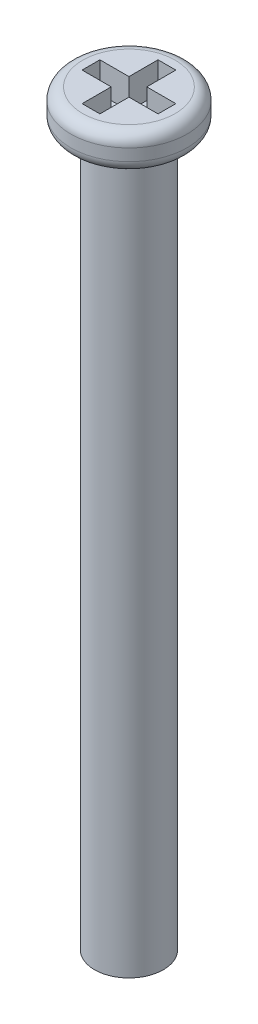
SolidWorks part; units mm, degrees
ref_plane "Front Plane" through (0, 0, 0) normal (0, 0, 1) x (1, 0, 0)
ref_plane "Top Plane" through (0, 0, 0) normal (0, 1, 0) x (1, 0, 0)
ref_plane "Right Plane" through (0, 0, 0) normal (1, 0, 0) x (0, 0, -1)
sketch "Sketch1" plane through (0, 0, 0) normal (0, 1, 0) x (1, 0, 0)
  circle A0 centre (0, 0) radius 1.45
  dimension "D1" = 2.9
extrude "Boss-Extrude1" add sketch "Sketch1" along normal blind 30
sketch "Sketch2" plane through (0, 30, 0) normal (0, 1, 0) x (1, 0, 0)
  circle A0 centre (0, 0) radius 2.45
  dimension "D1" = 4.9
extrude "Boss-Extrude2" add sketch "Sketch2" along normal blind 1.5
fillet "Fillet1" radius 0.5 2 edges at (0, 30, 2.45) (0, 31.5, 2.45)
sketch "Sketch3" plane through (0, 31.5, 0) normal (0, 1, 0) x (1, 0, 0)
  line L1 (-0.375, 1.6) -> (0.375, 1.6)
  line L2 (-0.375, 1.6) -> (-0.375, -1.6)
  line L3 (-0.375, -1.6) -> (0.375, -1.6)
  line L4 (0.375, 1.6) -> (0.375, -1.6)
  line L5 (-1.6, 0.375) -> (1.6, 0.375)
  line L6 (-1.6, 0.375) -> (-1.6, -0.375)
  line L7 (-1.6, -0.375) -> (1.6, -0.375)
  line L8 (1.6, 0.375) -> (1.6, -0.375)
  dimension "D1" = 0.75
  dimension "D2" = 0.75
  dimension "D3" = 3.2
  dimension "D4" = 3.2
  dimension "D5" = 1.6
  dimension "D6" = 0.375
  dimension "D7" = 1.6
  dimension "D8" = 0.375
extrude "Cut-Extrude1" cut sketch "Sketch3" against normal blind 1.25 contours L2 L5 L4 L1 | L2 L7 L4 L5 | L7 L2 L3 L4 | L8 L5 L4 L7 | L6 L7 L2 L5
fillet "Fillet4" radius 0.5 4 edges at (0, 30.25, 1.6) (1.6, 30.25, 0) (-1.6, 30.25, 0) (0, 30.25, -1.6)
